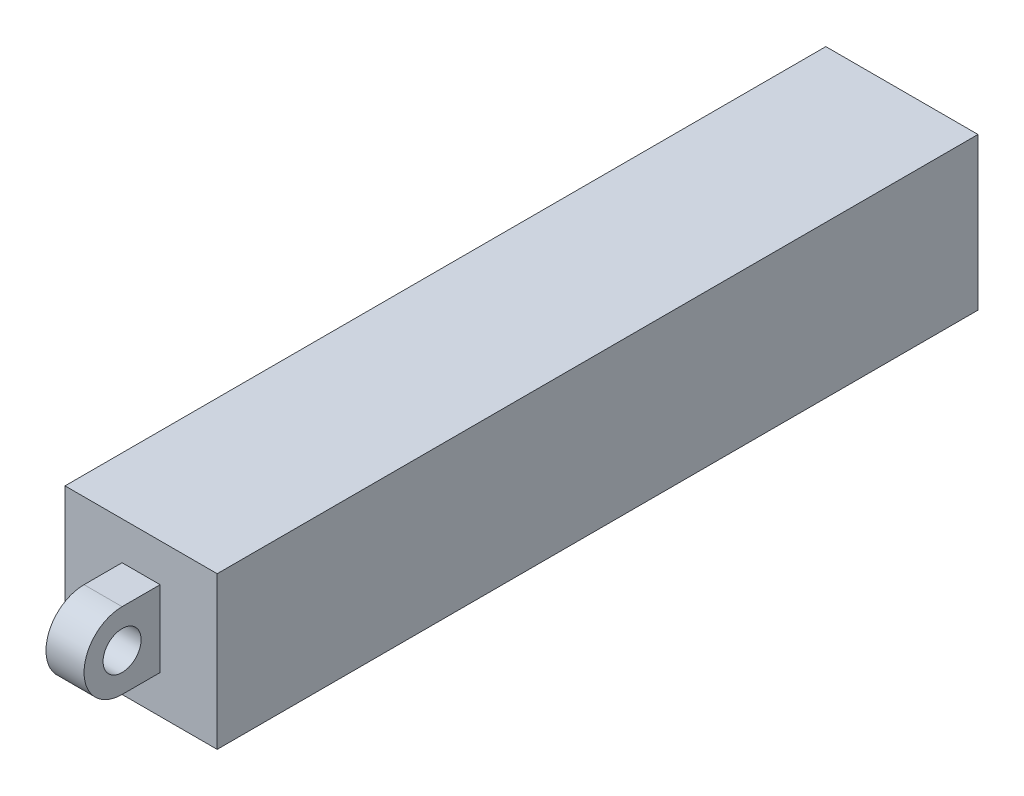
SolidWorks part; units mm, degrees
ref_plane "정면" through (0, 0, 0) normal (0, 0, 1) x (1, 0, 0)
ref_plane "윗면" through (0, 0, 0) normal (0, 1, 0) x (1, 0, 0)
ref_plane "우측면" through (0, 0, 0) normal (1, 0, 0) x (0, 0, -1)
sketch "스케치2" plane through (0, 0, 0) normal (1, 0, 0) x (0, 0, -1)
  line L0 (0, 5) -> (0, -5) construction
  line L1 (-25, 5) -> (25, 5)
  line L2 (-25, 5) -> (-25, -5)
  line L3 (-25, -5) -> (25, -5)
  line L4 (25, 5) -> (25, -5)
  line L5 (-25, 0) -> (25, 0) construction
  dimension "D1" = 10
  dimension "D2" = 50
extrude "보스-돌출1" add sketch "스케치2" along normal mid plane 10
sketch "스케치3" plane through (0, 0, 0) normal (1, 0, 0) x (0, 0, -1)
  line L0 (-25, 5) -> (-25, -5) construction
  line L1 (-27.5, 2.5) -> (-25, 2.5)
  line L2 (0, 0) -> (-168.2672, 0) construction
  line L3 (-27.5, -2.5) -> (-25, -2.5)
  line L4 (-25, 2.5) -> (-25, -2.5)
  arc A0 (-27.5, 2.5) -> (-27.5, -2.5) centre (-27.5, 0) ccw
  circle A1 centre (-27.5, 0) radius 1.25
  dimension "D3" = 2.5
  dimension "D1" = 5
  dimension "D2" = 2.5
extrude "보스-돌출2" add sketch "스케치3" along normal mid plane 2.5
